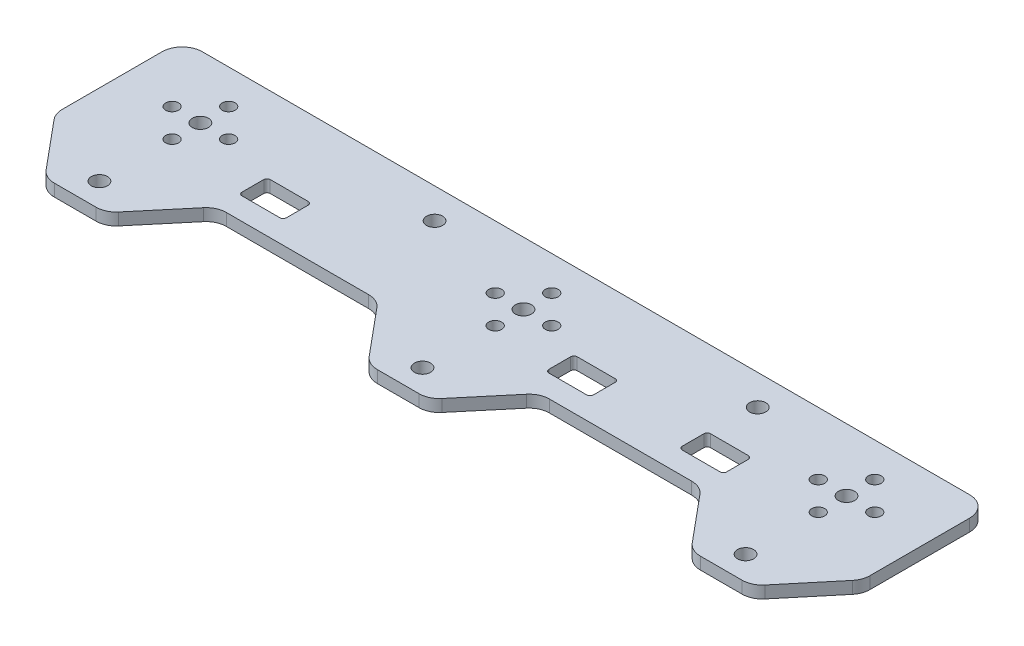
SolidWorks part; units mm, degrees
ref_plane "Front Plane" through (0, 0, 0) normal (0, 0, 1) x (1, 0, 0)
ref_plane "Top Plane" through (0, 0, 0) normal (0, 1, 0) x (1, 0, 0)
ref_plane "Right Plane" through (0, 0, 0) normal (1, 0, 0) x (0, 0, -1)
sketch "草图1" plane through (0, 0, 0) normal (0, 1, 0) x (1, 0, 0)
  line L1 (-100, -24) -> (100, -24)
  line L2 (-100, -24) -> (-100, 24)
  line L3 (-100, 24) -> (100, 24)
  line L4 (100, -24) -> (100, 24)
  line L5 (-100, -24) -> (100, 24) construction
  line L6 (-100, 24) -> (100, -24) construction
  point P0 (0, 0)
  dimension "D1" = 48
  dimension "D2" = 200
extrude "凸台-拉伸1" add sketch "草图1" along normal blind 3
sketch "草图2" plane through (0, 3, 0) normal (0, 1, 0) x (1, 0, 0)
  line L0 (0, 24) -> (0, -41.457) construction
  line L1 (100, 24) -> (-100, 24) construction
  line L2 (-100, 15) -> (100, 15) construction
  line L3 (-100, 24) -> (-100, -24) construction
  line L4 (100, -24) -> (100, 24) construction
  line L5 (-100, -18) -> (100, -18) construction
  line L6 (-100, -24) -> (100, -24) construction
  line L7 (-80, -18) -> (-80, 34.4329) construction
  circle A0 centre (-80, -18) radius 2
  circle A1 centre (0, -18) radius 2
  circle A2 centre (80, -18) radius 2
  circle A3 centre (-30, 15) radius 2
  circle A4 centre (50, 15) radius 2
  dimension "D3" = 4
  dimension "D4" = 20
  dimension "D5" = 4
  dimension "D6" = 30
  dimension "D7" = 4
  dimension "D8" = 4
  dimension "D9" = 50
  dimension "D1" = 33
  dimension "D2" = 6
extrude "切除-拉伸1" cut sketch "草图2" against normal blind 3
sketch "草图3" plane through (0, 3, 0) normal (0, 1, 0) x (1, 0, 0)
  line L0 (-80, -18) -> (-80, 32.9782) construction
  line L1 (0, -18) -> (0, 36.1593) construction
  line L2 (100, 24) -> (-100, 24) construction
  circle A0 centre (-80, 7) radius 10.5
  circle A1 centre (0, 7) radius 10.5
  circle A2 centre (80, 7) radius 10.5
  dimension "D1" = 21
  dimension "D2" = 17
  dimension "D3" = 17
  dimension "D4" = 21
extrude "切除-拉伸2" cut sketch "草图3" against normal blind 0.1
sketch "草图5" plane through (0, 3, 0) normal (0, 1, 0) x (1, 0, 0)
  line L0 (0, 29.4675) -> (0, -28.6812) construction
  line L1 (-90.5, 7) -> (90.5, 7) construction
  line L2 (-40, 38.4326) -> (-40, -33.8106) construction
  circle A0 centre (-80, 7) radius 10.5 construction
  circle A1 centre (-80, 7) radius 10.5 construction
  circle A2 centre (80, 7) radius 10.5 construction
  circle A3 centre (0, 7) radius 2
  circle A4 centre (0, 14) radius 1.6
  circle A5 centre (-7, 7) radius 1.6
  circle A6 centre (7, 7) radius 1.6
  circle A7 centre (0, 0) radius 1.6
  circle A9 centre (-80, 0) radius 1.6
  circle A10 centre (-87, 7) radius 1.6
  circle A11 centre (-73, 7) radius 1.6
  circle A12 centre (-80, 14) radius 1.6
  circle A13 centre (-80, 7) radius 2
  circle A14 centre (80, 7) radius 2
  circle A15 centre (80, 14) radius 1.6
  circle A16 centre (73, 7) radius 1.6
  circle A17 centre (87, 7) radius 1.6
  circle A18 centre (80, 0) radius 1.6
  dimension "D1" = 4
  dimension "D2" = 14
  dimension "D3" = 3.2
  dimension "D4" = 3.2
  dimension "D5" = 14
  dimension "D6" = 40
extrude "切除-拉伸3" cut sketch "草图5" against normal blind 10
sketch "草图7" plane through (0, 3, 0) normal (0, 1, 0) x (1, 0, 0)
  line L0 (-100, 24) -> (-100, -24) construction
  line L1 (100, 24) -> (-100, 24)
  line L2 (100, 24) -> (100, 22.5)
  line L3 (100, 22.5) -> (-100, 22.5)
  line L4 (-100, 24) -> (-100, 22.5)
  line L5 (100, 24) -> (-100, 22.5) construction
  line L6 (100, 22.5) -> (-100, 24) construction
  point P4 (0, 23.25)
  dimension "D1" = 1.5
extrude "切除-拉伸4" cut sketch "草图7" against normal blind 10
sketch "草图9" plane through (0, 3, 0) normal (0, 1, 0) x (1, 0, 0)
  circle A0 centre (-73, 7) radius 1.6 construction
  circle A1 centre (73, 7) radius 1.6
  circle A2 centre (73, 7) radius 1.6
  circle A3 centre (80, 14) radius 1.6
  circle A4 centre (80, 14) radius 1.6
  circle A5 centre (80, 7) radius 2
  circle A6 centre (80, 7) radius 2
  circle A7 centre (87, 7) radius 1.6
  circle A8 centre (87, 7) radius 1.6
  circle A9 centre (80, 0) radius 1.6
  circle A10 centre (80, 0) radius 1.6
  circle A11 centre (80, 7) radius 10.5
  circle A12 centre (80, 7) radius 10.5
  circle A13 centre (0, 7) radius 2
  circle A14 centre (0, 7) radius 2
  circle A15 centre (0, 14) radius 1.6
  circle A16 centre (0, 14) radius 1.6
  circle A17 centre (-7, 7) radius 1.6
  circle A18 centre (-7, 7) radius 1.6
  circle A19 centre (7, 7) radius 1.6
  circle A20 centre (7, 7) radius 1.6
  circle A21 centre (0, 0) radius 1.6
  circle A22 centre (0, 0) radius 1.6
  circle A23 centre (0, 7) radius 10.5
  circle A24 centre (0, 7) radius 10.5
  circle A25 centre (-80, 7) radius 10.5
  circle A26 centre (-80, 7) radius 10.5
  circle A27 centre (-80, 14) radius 1.6 construction
  circle A28 centre (-80, 0) radius 1.6 construction
  circle A29 centre (-87, 7) radius 1.6 construction
  circle A30 centre (-87, 7) radius 1.6
  circle A31 centre (-80, 0) radius 1.6
  circle A32 centre (-80, 14) radius 1.6
  circle A33 centre (-73, 7) radius 1.6
  circle A34 centre (-80, 7) radius 2 construction
  circle A35 centre (-80, 7) radius 2
  dimension "D1" = 0
  dimension "D2" = 0
  dimension "D3" = 0
  dimension "D4" = 0
  dimension "D5" = 0
  dimension "D6" = 0
  dimension "D7" = 0
  dimension "D8" = 0
  dimension "D9" = 0
  dimension "D10" = 0
  dimension "D11" = 0
  dimension "D12" = 0
  dimension "D13" = 0
extrude "凸台-拉伸3" add sketch "草图9" against normal up to surface (0.1 mm away) up to face at (0, 2.9, 1.6)
sketch "草图10" plane through (0, 0, 0) normal (0, -1, 0) x (1, 0, 0)
  line L0 (-111.5257, 69) -> (103.0871, 69) construction
  line L1 (100, -22.5) -> (-100, -22.5) construction
  line L2 (-117.1, 15) -> (103.0871, 15) construction
  line L3 (0, -70.4994) -> (0, 130.7165) construction
  line L4 (-25, -91.7959) -> (-25, 155.3177) construction
  line L5 (43, -85.5538) -> (43, 155.3177) construction
  line L6 (-100, 9) -> (-87.5, 24)
  line L7 (-100, -22.5) -> (-100, 24) construction
  line L8 (-100, 24) -> (100, 24) construction
  line L9 (-72.5, 24) -> (-7.5, 24)
  line L10 (-72.5, 24) -> (-59.9135, 9)
  line L11 (-59.9135, 9) -> (-20, 9)
  line L12 (-20, 9) -> (-7.5, 24)
  line L13 (72.5, 24) -> (7.5, 24)
  line L14 (7.5, 24) -> (20.0865, 9)
  line L15 (20.0865, 9) -> (60, 9)
  line L16 (60, 9) -> (72.5, 24)
  line L18 (87.5, 24) -> (100, 9)
  line L19 (100, 24) -> (100, -22.5) construction
  line L20 (-80, -7) -> (-80, 38.6844) construction
  line L21 (80, -7) -> (80, 34.5372) construction
  line L22 (-100, 9) -> (-100, 24)
  line L23 (-100, 24) -> (-87.5, 24)
  line L26 (100, 9) -> (100, 24)
  line L27 (100, 24) -> (87.5, 24)
  circle A0 centre (-25, 15) radius 1.5 construction
  circle A1 centre (43, 15) radius 1.5 construction
  circle A2 centre (-80, 0) radius 1.6 construction
  circle A3 centre (80, 0) radius 1.6 construction
  dimension "D5" = 3
  dimension "D6" = 3
  dimension "D1" = 91.5
  dimension "D2" = 54
  dimension "D3" = 25
  dimension "D4" = 68
  dimension "D7" = 15
  dimension "D8" = 9
  dimension "D9" = 9
  dimension "D10" = 15
  dimension "D11" = 15
  dimension "D12" = 9
  dimension "D13" = 50
extrude "翅膀孔位" cut sketch "草图10" against normal blind 10
sketch "草图11" plane through (0, 0, 0) normal (0, -1, 0) x (1, 0, 0)
  line L0 (-100, 0) -> (108.6878, 0) construction
  line L1 (-100, -22.5) -> (-100, 9) construction
  line L2 (-80, -12.4) -> (-80, 38.1489) construction
  line L3 (0, -41.4672) -> (0, 70.2615) construction
  line L4 (-49, -3.5) -> (-60, -3.5)
  line L5 (-49, -3.5) -> (-49, 3.5)
  line L6 (-49, 3.5) -> (-60, 3.5)
  line L7 (-60, -3.5) -> (-60, 3.5)
  line L8 (-49, -3.5) -> (-60, 3.5) construction
  line L9 (-49, 3.5) -> (-60, -3.5) construction
  line L10 (80, -15.6) -> (80, 54.8928) construction
  line L11 (27, -3.5) -> (16, -3.5)
  line L12 (27, -3.5) -> (27, 3.5)
  line L13 (27, 3.5) -> (16, 3.5)
  line L14 (16, -3.5) -> (16, 3.5)
  line L15 (27, -3.5) -> (16, 3.5) construction
  line L16 (27, 3.5) -> (16, -3.5) construction
  line L17 (60, -3.5) -> (49, -3.5)
  line L18 (60, -3.5) -> (60, 3.5)
  line L19 (60, 3.5) -> (49, 3.5)
  line L20 (49, -3.5) -> (49, 3.5)
  line L21 (60, -3.5) -> (49, 3.5) construction
  line L22 (60, 3.5) -> (49, -3.5) construction
  circle A0 centre (-80, -14) radius 1.6 construction
  circle A1 centre (80, -14) radius 1.6 construction
  point P10 (-54.5, 0)
  point P17 (21.5, 0)
  point P22 (54.5, 0)
  dimension "D1" = 7
  dimension "D2" = 11
  dimension "D3" = 20
  dimension "D4" = 7
  dimension "D5" = 11
  dimension "D6" = 16
  dimension "D7" = 20
  dimension "D8" = 7
  dimension "D9" = 11
extrude "切除-拉伸6" cut sketch "草图11" against normal blind 10
fillet "圆角1" radius 5 2 edges at (100, 1.5, -22.5) (-100, 1.5, -22.5)
fillet "圆角2" radius 5 12 edges at (100, 1.5, 9) (87.5, 1.5, 24) (72.5, 1.5, 24) (60, 1.5, 9) (20.0865, 1.5, 9) (7.5, 1.5, 24) (-7.5, 1.5, 24) (-20, 1.5, 9) (-59.9135, 1.5, 9) (-72.5, 1.5, 24) (-87.5, 1.5, 24) (-100, 1.5, 9)
fillet "圆角3" radius 0.8 12 edges at (-49, 1.5, 3.5) (-49, 1.5, -3.5) (-60, 1.5, -3.5) (-60, 1.5, 3.5) (16, 1.5, 3.5) (16, 1.5, -3.5) (27, 1.5, -3.5) (27, 1.5, 3.5) (60, 1.5, 3.5) (49, 1.5, 3.5) (49, 1.5, -3.5) (60, 1.5, -3.5)
